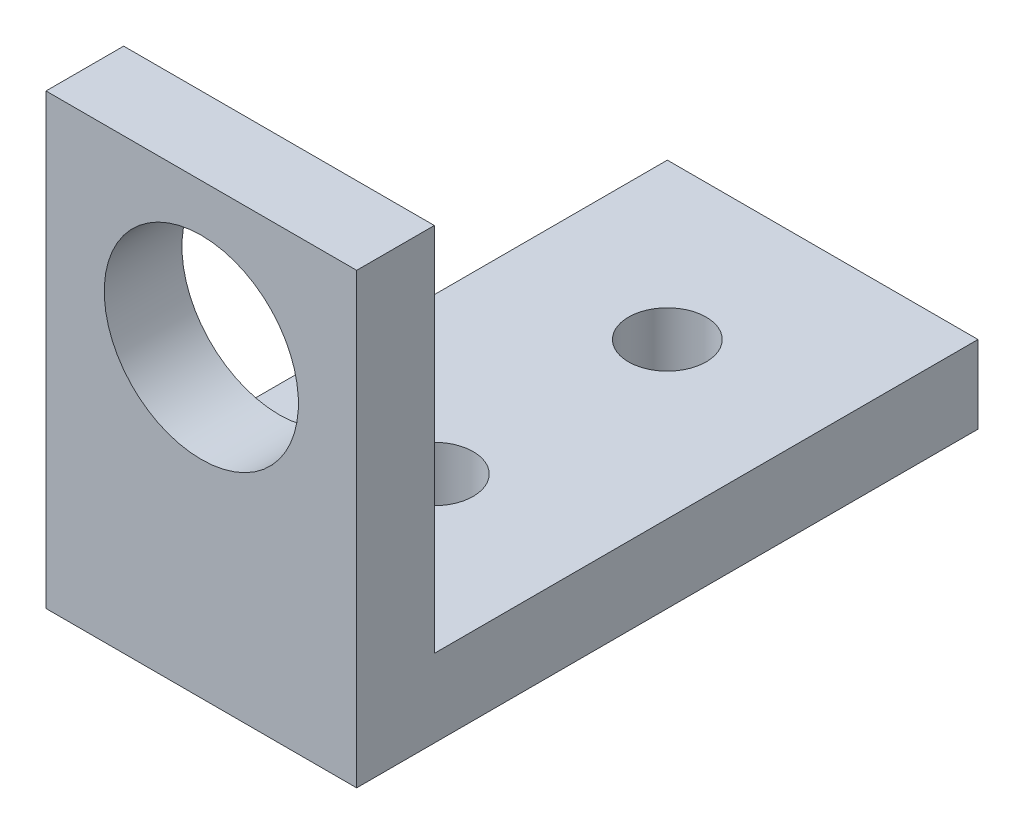
SolidWorks part; units mm, degrees
ref_plane "Front Plane" through (0, 0, 0) normal (0, 0, 1) x (1, 0, 0)
ref_plane "Top Plane" through (0, 0, 0) normal (0, 1, 0) x (1, 0, 0)
ref_plane "Right Plane" through (0, 0, 0) normal (1, 0, 0) x (0, 0, -1)
sketch "Sketch1" plane through (0, 0, 0) normal (1, 0, 0) x (0, 0, -1)
  line L0 (0, 76.2) -> (0, 0)
  line L1 (0, 0) -> (50.8, 0)
  line L2 (6.35, 76.2) -> (6.35, 6.35)
  line L3 (6.35, 6.35) -> (50.8, 6.35)
  line L4 (0, 76.2) -> (6.35, 76.2)
  line L5 (50.8, 6.35) -> (50.8, 0)
  dimension "D1" = 76.2
  dimension "D2" = 50.8
  dimension "D3" = 6.35
extrude "Boss-Extrude1" add sketch "Sketch1" along normal blind 25.4
sketch "Sketch2" plane through (0, 6.35, 0) normal (0, 1, 0) x (1, 0, 0)
  line L1 (25.4, 6.35) -> (0, 6.35) construction
  circle A0 centre (12.7, 38.1) radius 3.175
  circle A1 centre (12.7, 19.05) radius 3.175
  dimension "D1" = 12.7
  dimension "D2" = 31.75
  dimension "D3" = 6.35
extrude "Cut-Extrude1" cut sketch "Sketch2" against normal up to next
hole_wizard "5/8 (0.625) Diameter Hole1" positions "Sketch4" profile "Sketch3" hole size "5/8" standard "ANSI Inch" end condition up to next
sketch "Sketch4" plane through (0, 0, -6.35) normal (0, 0, -1) x (-1, 0, 0)
  line L0 (-25.4, 0) -> (0, 0) construction
  line L1 (-25.4, 6.35) -> (-25.4, 76.2) construction
  point P0 (-12.7, 57.15)
  point P2 (-12.7, 24.8412)
  dimension "D1" = 57.15
  dimension "D2" = 12.7
  dimension "D3" = 24.8412
  dimension "D4" = 12.7
sketch "Sketch3" plane through (12.7, 57.15, -6.35) normal (1, 0, 0) x (0, 1, 0)
  line L0 (0, 0) -> (0, 6.35)
  line L1 (0, 6.35) -> (7.9375, 6.35)
  line L2 (7.9375, 6.35) -> (7.9375, 0)
  line L5 (7.9375, 0) -> (0, 0)
  line L11 (0, -6.35) -> (0, 107.95) construction
  dimension "Thru Hole Dia." = 15.875
  dimension "Thru Hole Depth" = 6.35
sketch "Sketch5" plane through (0, 0, 0) normal (0, 0, 1) x (1, 0, 0)
  line L0 (25.4, 76.2) -> (25.4, 0) construction
  line L1 (0, 76.2) -> (25.4, 76.2)
  line L2 (0, 76.2) -> (0, 36.6475)
  line L3 (0, 36.6475) -> (25.4, 36.6475)
  line L4 (25.4, 76.2) -> (25.4, 36.6475)
extrude "Cut-Extrude2" cut sketch "Sketch5" against normal up to next
